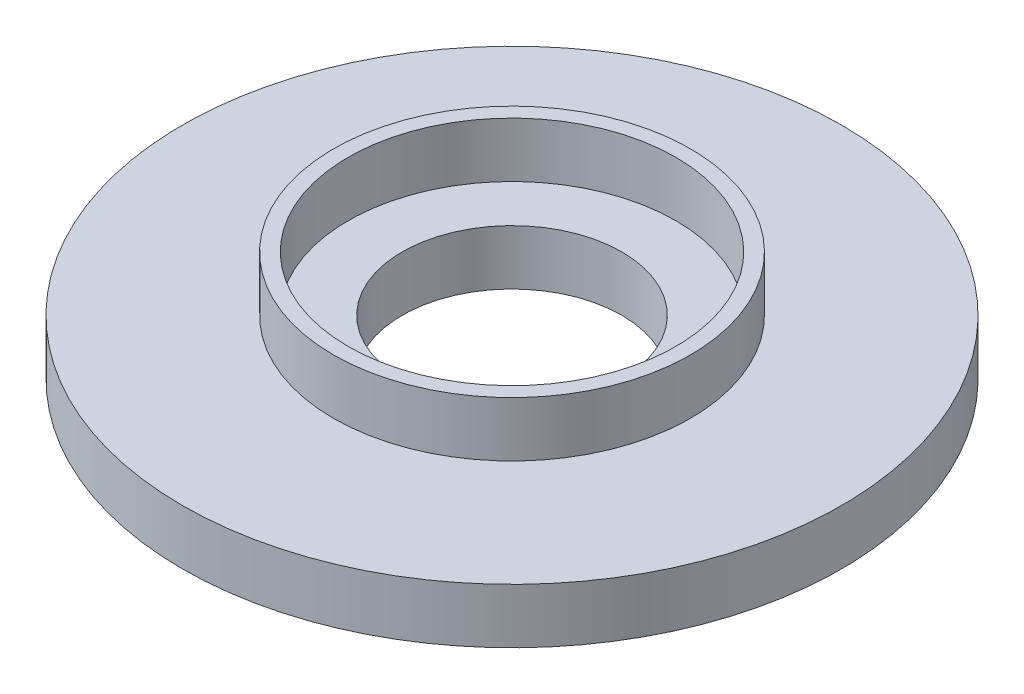
SolidWorks part; units mm, degrees
ref_plane "Front Plane" through (0, 0, 0) normal (0, 0, 1) x (1, 0, 0)
ref_plane "Top Plane" through (0, 0, 0) normal (0, 1, 0) x (1, 0, 0)
ref_plane "Right Plane" through (0, 0, 0) normal (1, 0, 0) x (0, 0, -1)
sketch "Sketch1" plane through (0, 0, 0) normal (0, 1, 0) x (1, 0, 0)
  circle A0 centre (0, 0) radius 18
  circle A1 centre (0, 0) radius 6
  dimension "D1" = 36
  dimension "D2" = 12
extrude "Boss-Extrude1" add sketch "Sketch1" along normal blind 3
sketch "Sketch2" plane through (0, 3, 0) normal (0, 1, 0) x (1, 0, 0)
  circle A0 centre (0, 0) radius 9.75
  circle A1 centre (0, 0) radius 8.95
  dimension "D1" = 19.5
  dimension "D2" = 0.8
extrude "Boss-Extrude2" add sketch "Sketch2" along normal blind 3
